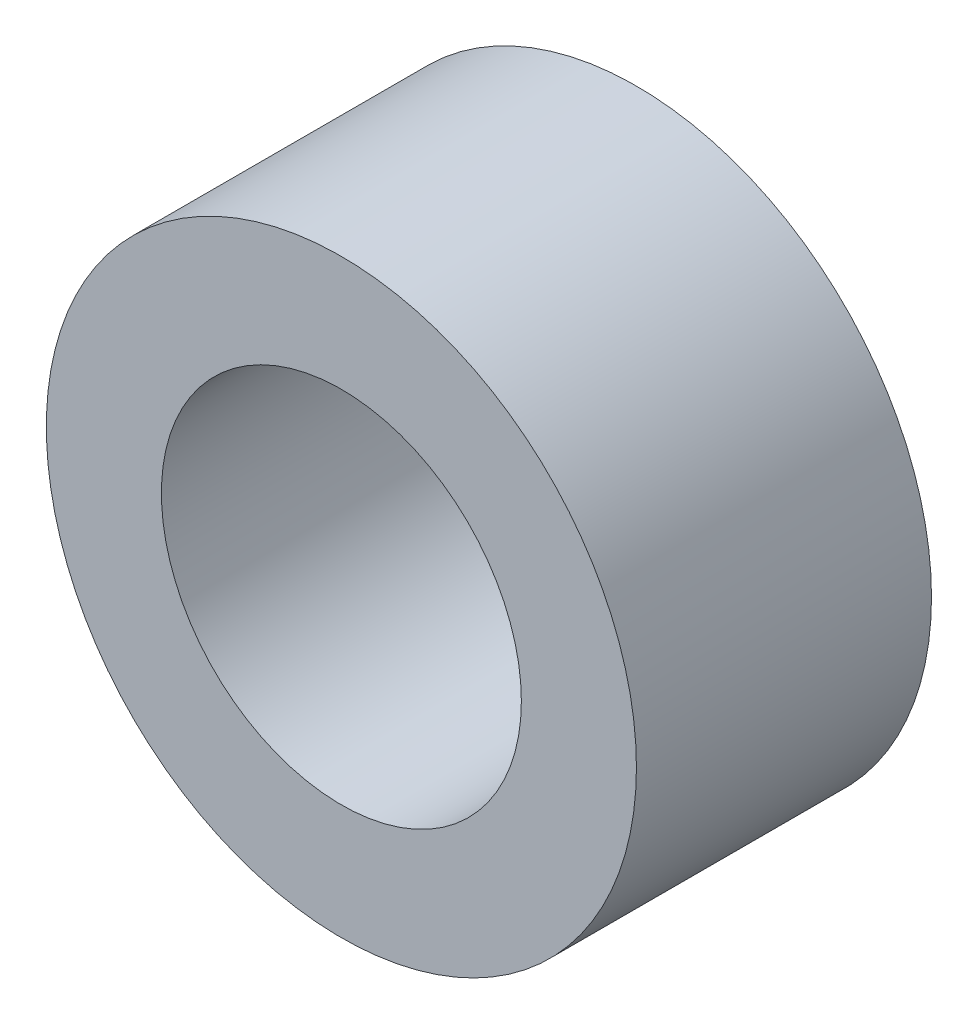
SolidWorks part; units mm, degrees
ref_plane "Front Plane" through (0, 0, 0) normal (0, 0, 1) x (1, 0, 0)
ref_plane "Top Plane" through (0, 0, 0) normal (0, 1, 0) x (1, 0, 0)
ref_plane "Right Plane" through (0, 0, 0) normal (1, 0, 0) x (0, 0, -1)
sketch "Sketch1" plane through (0, 0, 0) normal (0, 0, 1) x (1, 0, 0)
  circle A0 centre (0, 0) radius 5
  circle A1 centre (0, 0) radius 3.05
  dimension "D1" = 10
  dimension "D2" = 6.1
extrude "Boss-Extrude1" add sketch "Sketch1" along normal blind 5
